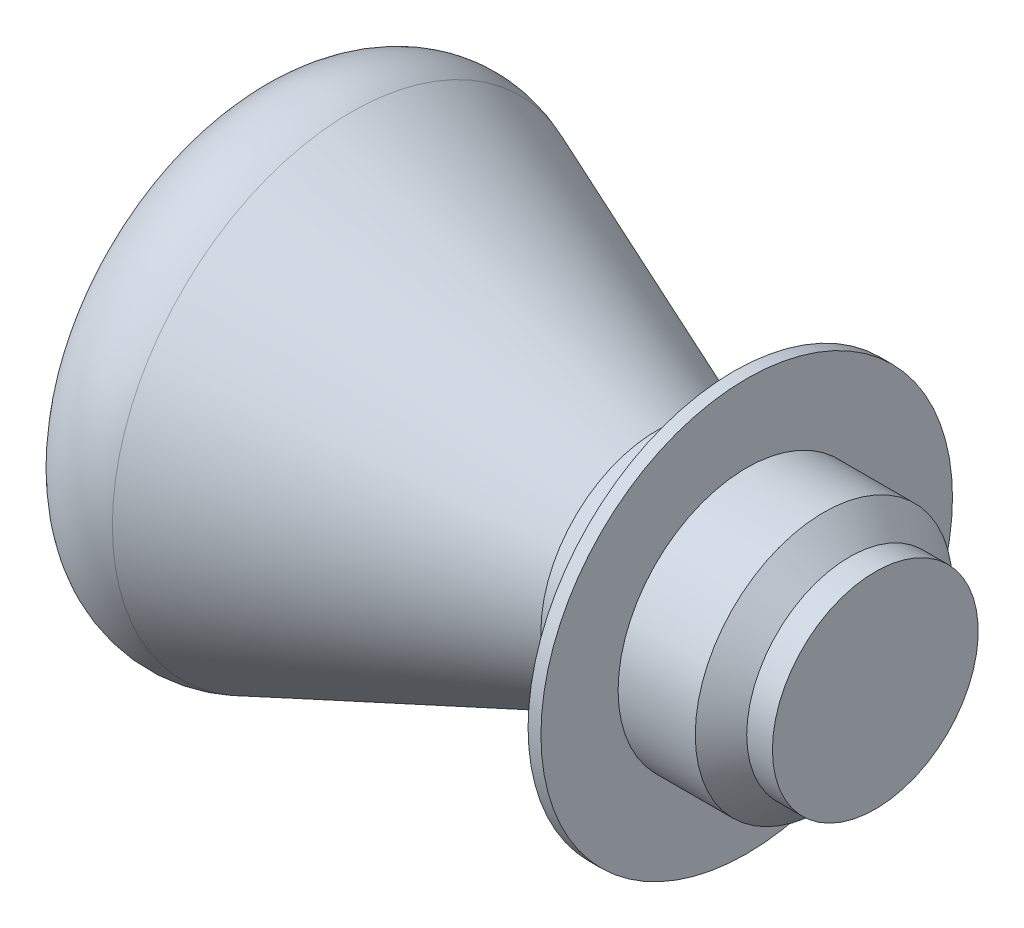
SolidWorks part; units mm, degrees
ref_plane "Front Plane" through (0, 0, 0) normal (0, 0, 1) x (1, 0, 0)
ref_plane "Top Plane" through (0, 0, 0) normal (0, 1, 0) x (1, 0, 0)
ref_plane "Right Plane" through (0, 0, 0) normal (1, 0, 0) x (0, 0, -1)
sketch "Sketch1" plane through (0, 0, 0) normal (0, 0, 1) x (1, 0, 0)
  line L0 (0, 0) -> (5.5, 0)
  line L1 (5.5, 0) -> (5.5, 4)
  line L2 (5.5, 4) -> (4.5, 4)
  line L3 (4.5, 4) -> (3.5, 5)
  line L4 (3.5, 5) -> (0.5, 5)
  line L5 (0.5, 5) -> (0.5, 8)
  line L6 (0.5, 8) -> (0, 8)
  line L7 (0, 8) -> (0, 5)
  line L8 (0, 5) -> (-2, 5)
  line L9 (-2, 5) -> (-2, 4.5)
  line L10 (-2, 4.5) -> (0, 4.5)
  line L11 (0, 4.5) -> (0, 0)
  dimension "D1" = 5.5
  dimension "D2" = 5
  dimension "D3" = 1
  dimension "D4" = 1
  dimension "D5" = 3
  dimension "D6" = 0.5
  dimension "D7" = 3
  dimension "D8" = 2
  dimension "D9" = 0.5
revolve "Revolve1" add sketch "Sketch1" angle 360 about L0
sketch "Sketch2" plane through (0, 0, 0) normal (0, 0, 1) x (1, 0, 0)
  line L0 (0, 0) -> (-19.8585, 0) construction
  line L1 (0, 0) -> (0, 4.5)
  line L2 (0, 4.5) -> (-3, 4.5)
  line L3 (-3, 4.5) -> (-14.8796, 9.2829)
  line L4 (-19.8585, 0) -> (0, 0)
  arc A0 (-18.8971, 7.2789) -> (-19.8585, 0) centre (8.1769, 0) ccw
  arc A1 (-14.8796, 9.2829) -> (-18.8971, 7.2789) centre (-16, 6.5) ccw
  point P10 (-19.8456, 0)
  dimension "D1" = 3
  dimension "D2" = 16
  dimension "D3" = 2
  dimension "D5" = 3
revolve "Revolve2" add sketch "Sketch2" angle 360 about L4
